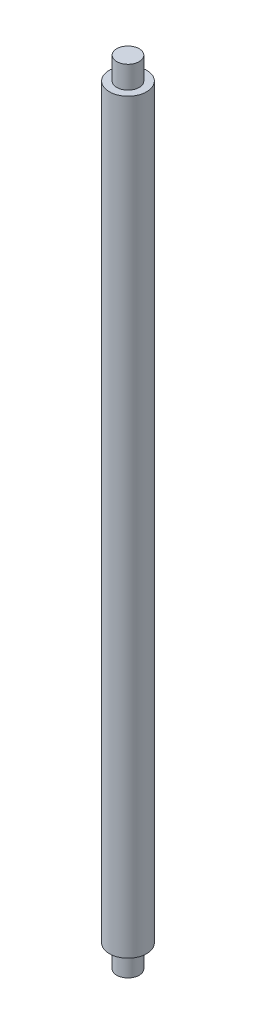
SolidWorks part; units mm, degrees
ref_plane "前视基准面" through (0, 0, 0) normal (0, 0, 1) x (1, 0, 0)
ref_plane "上视基准面" through (0, 0, 0) normal (0, 1, 0) x (1, 0, 0)
ref_plane "右视基准面" through (0, 0, 0) normal (1, 0, 0) x (0, 0, -1)
other "Configuration Table"
sketch "草图1" plane through (0, 0, 0) normal (0, 1, 0) x (1, 0, 0)
  circle A0 centre (0, 0) radius 2.5
  dimension "D1" = 5
extrude "凸台-拉伸2" add sketch "草图1" against normal mid plane 100
sketch "草图2" plane through (0, 50, 0) normal (0, 1, 0) x (1, 0, 0)
  circle A0 centre (0, 0) radius 1.5
  dimension "D1" = 3
extrude "凸台-拉伸3" add sketch "草图2" along normal blind 3
sketch "草图3" plane through (0, -50, 0) normal (0, -1, 0) x (1, 0, 0)
  circle A0 centre (0, 0) radius 1.5
  dimension "D1" = 3
extrude "凸台-拉伸4" add sketch "草图3" along normal blind 3
